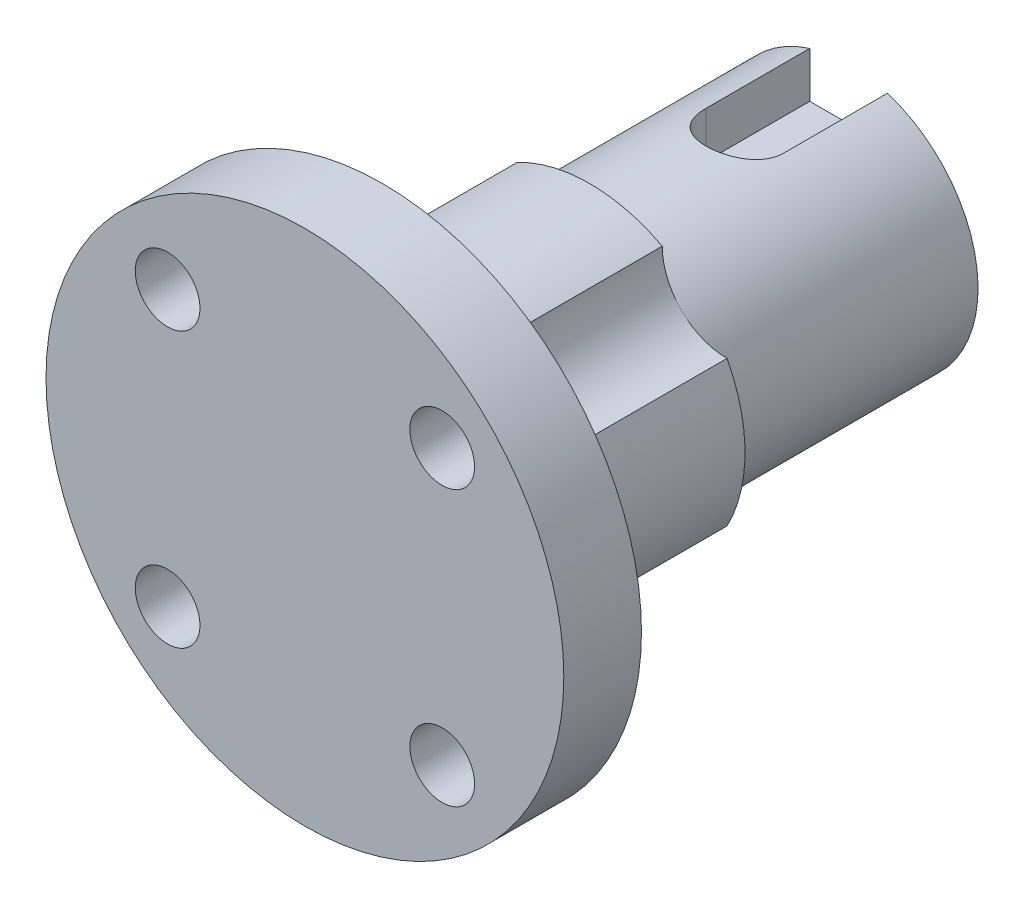
SolidWorks part; units mm, degrees
ref_plane "前视基准面" through (0, 0, 0) normal (0, 0, 1) x (1, 0, 0)
ref_plane "上视基准面" through (0, 0, 0) normal (0, 1, 0) x (1, 0, 0)
ref_plane "右视基准面" through (0, 0, 0) normal (1, 0, 0) x (0, 0, -1)
sketch "草图1" plane through (0, 0, 0) normal (0, 0, 1) x (1, 0, 0)
  circle A0 centre (0, 0) radius 5
  dimension "D1" = 10
extrude "凸台-拉伸1" add sketch "草图1" along normal blind 10
ref_plane "基准面4" through (0, 5, 0) normal (0, 1, 0) x (1, 0, 0)
sketch "草图2" plane through (0, 5, 0) normal (0, 1, 0) x (1, 0, 0)
  line L0 (0, 0) -> (0, -10) construction
  line L1 (-5, -10) -> (5, -10) construction
  line L2 (0, -4) -> (0, 0) construction
  line L3 (-1.5, -4) -> (-1.5, 0)
  line L4 (1.5, -4) -> (1.5, 0)
  line L6 (-1.5, 0) -> (1.5, 0)
  line L7 (-1.5, -4) -> (1.5, -4) construction
  line L8 (5, 0) -> (-5, 0) construction
  arc A0 (-1.5, -4) -> (1.5, -4) centre (0, -4) ccw
  arc A1 (0, 1.5) -> (-1.5, 0) centre (0, 0) ccw construction
  arc A2 (1.5, 0) -> (0, 1.5) centre (0, 0) ccw construction
  point P7 (0, -3.5)
  dimension "D1" = 3
  dimension "D2" = 4
extrude "切除-拉伸1" cut sketch "草图2" against normal blind 2
sketch "草图3" plane through (0, 0, 10) normal (0, 0, 1) x (1, 0, 0)
  circle A0 centre (0, 0) radius 6
  dimension "D1" = 12
extrude "凸台-拉伸2" add sketch "草图3" along normal blind 8
sketch "草图4" plane through (0, 0, 0) normal (0, 0, -1) x (-1, 0, 0)
  circle A0 centre (0, 0) radius 1.25
  dimension "D1" = 2.5
extrude "切除-拉伸2" cut sketch "草图4" against normal blind 10
sketch "草图6" plane through (0, 0, 18) normal (0, 0, 1) x (1, 0, 0)
  circle A0 centre (0, 0) radius 10
  dimension "D1" = 20
extrude "凸台-拉伸3" add sketch "草图6" along normal blind 3
sketch "草图7" plane through (0, 0, 18) normal (0, 0, -1) x (-1, 0, 0)
  line L0 (-5.3033, -5.3033) -> (5.3033, 5.3033) construction
  line L1 (-5.3033, 5.3033) -> (5.3033, -5.3033) construction
  line L2 (0, 0) -> (-7.5, 0) construction
  circle A0 centre (0, 0) radius 7.5 construction
  circle A1 centre (5.3033, 5.3033) radius 1.25
  circle A2 centre (-5.3033, 5.3033) radius 1.25
  circle A3 centre (-5.3033, -5.3033) radius 1.25
  circle A4 centre (5.3033, -5.3033) radius 1.25
  dimension "D1" = 15
  dimension "D2" = 2.5
  dimension "D3" = 45
extrude "切除-拉伸4" cut sketch "草图7" against normal up to next
cosmetic thread "装饰螺纹线1" parameters "D2"=3
cosmetic thread "装饰螺纹线2" parameters "D2"=3
cosmetic thread "装饰螺纹线3" parameters "D2"=3
cosmetic thread "装饰螺纹线4" parameters "D2"=3
sketch "草图11" plane through (0, 0, 18) normal (0, 0, -1) x (-1, 0, 0)
  circle A0 centre (5.3033, 5.3033) radius 2.5
  circle A1 centre (-5.3033, 5.3033) radius 2.5
  circle A2 centre (-5.3033, -5.3033) radius 2.5
  circle A3 centre (5.3033, -5.3033) radius 2.5
  dimension "D1" = 5
extrude "切除-拉伸5" cut sketch "草图11" along normal up to next
